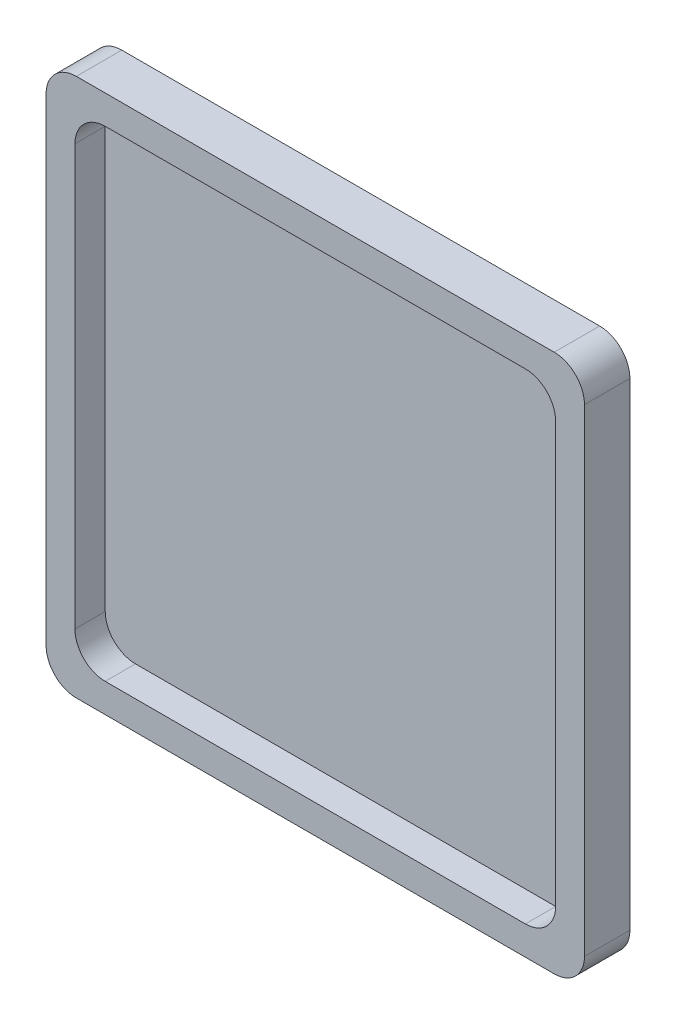
SolidWorks part; units mm, degrees
ref_plane "Front Plane" through (0, 0, 0) normal (0, 0, 1) x (1, 0, 0)
ref_plane "Top Plane" through (0, 0, 0) normal (0, 1, 0) x (1, 0, 0)
ref_plane "Right Plane" through (0, 0, 0) normal (1, 0, 0) x (0, 0, -1)
sketch "Sketch1" plane through (0, 0, 0) normal (0, 0, 1) x (1, 0, 0)
  line L1 (8.886, 138.2827) -> (186.686, 138.2827)
  line L2 (8.886, 138.2827) -> (8.886, -39.5173)
  line L3 (8.886, -39.5173) -> (186.686, -39.5173)
  line L4 (186.686, 138.2827) -> (186.686, -39.5173)
  dimension "D1" = 177.8
  dimension "D2" = 177.8
extrude "Boss-Extrude1" add sketch "Sketch1" along normal blind 15
sketch "Sketch2" plane through (0, 0, 15) normal (0, 0, 1) x (1, 0, 0)
  line L0 (8.886, -39.5173) -> (186.686, -39.5173) construction
  line L1 (177.161, -29.9923) -> (18.411, -29.9923)
  line L2 (177.161, -29.9923) -> (177.161, 128.7577)
  line L3 (177.161, 128.7577) -> (18.411, 128.7577)
  line L4 (18.411, -29.9923) -> (18.411, 128.7577)
  line L5 (186.686, -39.5173) -> (186.686, 138.2827) construction
  dimension "D1" = 158.75
  dimension "D2" = 158.75
  dimension "D3" = 9.525
  dimension "D4" = 9.525
extrude "Cut-Extrude1" cut sketch "Sketch2" against normal blind 10
fillet "Fillet1" radius 10 8 edges at (186.686, -39.5173, 7.5) (18.411, 128.7577, 10) (177.161, 128.7577, 10) (18.411, -29.9923, 10) (177.161, -29.9923, 10) (186.686, 138.2827, 7.5) (8.886, -39.5173, 7.5) (8.886, 138.2827, 7.5)
sketch "Sketch3" plane through (0, 0, 0) normal (0, 0, -1) x (-1, 0, 0)
  line L0 (-186.686, -29.5173) -> (-186.686, 128.2827) construction
  line L1 (-129.536, 17.6327) -> (-66.036, 17.6327)
  line L2 (-129.536, 17.6327) -> (-129.536, 81.1327)
  line L3 (-129.536, 81.1327) -> (-66.036, 81.1327)
  line L4 (-66.036, 17.6327) -> (-66.036, 81.1327)
  line L5 (-18.886, -39.5173) -> (-176.686, -39.5173) construction
  dimension "D1" = 63.5
  dimension "D2" = 63.5
  dimension "D3" = 57.15
  dimension "D4" = 57.15
extrude "Boss-Extrude2" add sketch "Sketch3" along normal blind 10
